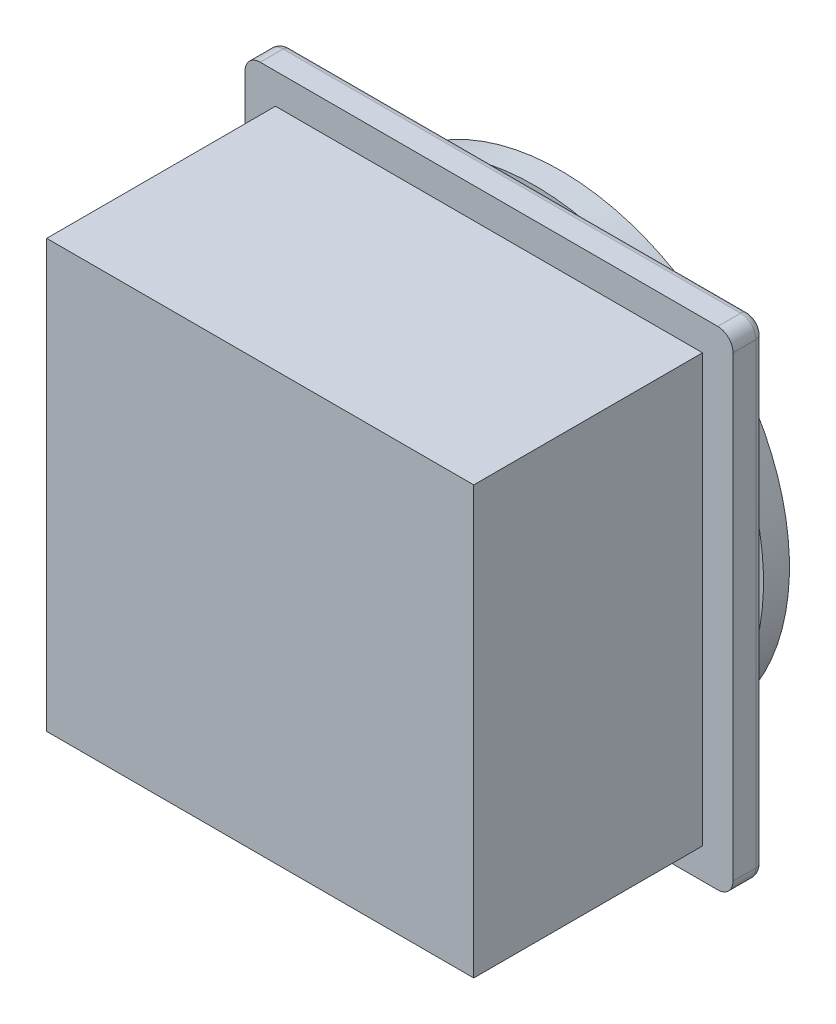
SolidWorks part; units mm, degrees
ref_plane "前视基准面" through (0, 0, 0) normal (0, 0, 1) x (1, 0, 0)
ref_plane "上视基准面" through (0, 0, 0) normal (0, 1, 0) x (1, 0, 0)
ref_plane "右视基准面" through (0, 0, 0) normal (1, 0, 0) x (0, 0, -1)
sketch "草图1" plane through (0, 0, 0) normal (0, 0, 1) x (1, 0, 0)
  line L1 (-140, 140) -> (140, 140)
  line L2 (-140, 140) -> (-140, -140)
  line L3 (-140, -140) -> (140, -140)
  line L4 (140, 140) -> (140, -140)
  line L5 (-140, 140) -> (140, -140) construction
  line L6 (-140, -140) -> (140, 140) construction
  point P0 (0, 0)
  dimension "D1" = 280
  dimension "D2" = 280
extrude "凸台-拉伸1" add sketch "草图1" along normal blind 150
sketch "草图2" plane through (0, -140, 0) normal (0, -1, 0) x (1, 0, 0)
  line L0 (-100.8552, 105.7202) -> (-100.8552, 55.7202)
  line L1 (-95.8552, 55.7202) -> (-95.8552, 105.7202)
  line L4 (-70.8552, 105.7202) -> (-70.8552, 55.7202)
  line L5 (-65.8552, 55.7202) -> (-65.8552, 105.7202)
  line L6 (-40.8552, 105.7202) -> (-40.8552, 55.7202)
  line L7 (-35.8552, 55.7202) -> (-35.8552, 105.7202)
  line L8 (-10.8552, 105.7202) -> (-10.8552, 55.7202)
  line L9 (-5.8552, 55.7202) -> (-5.8552, 105.7202)
  line L10 (19.1448, 105.7202) -> (19.1448, 55.7202)
  line L11 (24.1448, 55.7202) -> (24.1448, 105.7202)
  line L12 (49.1448, 105.7202) -> (49.1448, 55.7202)
  line L13 (54.1448, 55.7202) -> (54.1448, 105.7202)
  line L14 (79.1448, 105.7202) -> (79.1448, 55.7202)
  line L15 (84.1448, 55.7202) -> (84.1448, 105.7202)
  line L16 (109.1448, 105.7202) -> (109.1448, 55.7202)
  line L17 (114.1448, 55.7202) -> (114.1448, 105.7202)
  arc A0 (-100.8552, 55.7202) -> (-95.8552, 55.7202) centre (-98.3552, 55.7202) ccw
  arc A1 (-95.8552, 105.7202) -> (-100.8552, 105.7202) centre (-98.3552, 105.7202) ccw
  arc A2 (-65.8552, 105.7202) -> (-70.8552, 105.7202) centre (-68.3552, 105.7202) ccw
  arc A3 (-70.8552, 55.7202) -> (-65.8552, 55.7202) centre (-68.3552, 55.7202) ccw
  arc A4 (-35.8552, 105.7202) -> (-40.8552, 105.7202) centre (-38.3552, 105.7202) ccw
  arc A5 (-40.8552, 55.7202) -> (-35.8552, 55.7202) centre (-38.3552, 55.7202) ccw
  arc A6 (-5.8552, 105.7202) -> (-10.8552, 105.7202) centre (-8.3552, 105.7202) ccw
  arc A7 (-10.8552, 55.7202) -> (-5.8552, 55.7202) centre (-8.3552, 55.7202) ccw
  arc A8 (24.1448, 105.7202) -> (19.1448, 105.7202) centre (21.6448, 105.7202) ccw
  arc A9 (19.1448, 55.7202) -> (24.1448, 55.7202) centre (21.6448, 55.7202) ccw
  arc A10 (54.1448, 105.7202) -> (49.1448, 105.7202) centre (51.6448, 105.7202) ccw
  arc A11 (49.1448, 55.7202) -> (54.1448, 55.7202) centre (51.6448, 55.7202) ccw
  arc A12 (84.1448, 105.7202) -> (79.1448, 105.7202) centre (81.6448, 105.7202) ccw
  arc A13 (79.1448, 55.7202) -> (84.1448, 55.7202) centre (81.6448, 55.7202) ccw
  arc A14 (114.1448, 105.7202) -> (109.1448, 105.7202) centre (111.6448, 105.7202) ccw
  arc A15 (109.1448, 55.7202) -> (114.1448, 55.7202) centre (111.6448, 55.7202) ccw
  dimension "D1" = 5
  dimension "D3" = 8
  dimension "D2" = 50
shell "抽壳2" thickness 10
extrude "切除-拉伸2" cut sketch "草图2" against normal blind 10
sketch "草图3" plane through (0, 0, 0) normal (0, 0, -1) x (-1, 0, 0)
  line L8 (-160, 160) -> (-160, -160)
  line L9 (-160, -160) -> (160, -160)
  line L10 (160, -160) -> (160, 160)
  line L11 (160, 160) -> (-160, 160)
  line L12 (-160, 160) -> (-160, -160)
  line L13 (-160, -160) -> (160, -160)
  line L14 (160, -160) -> (160, 160)
  line L15 (160, 160) -> (-160, 160)
  dimension "D1" = 20
extrude "凸台-拉伸2" add sketch "草图3" along normal blind 20
fillet "圆角1" radius 10 1 edges at (-160, -160, -10)
fillet "圆角2" radius 10 3 edges at (160, -160, -10) (160, 160, -10) (-160, 160, -10)
fillet "圆角3" radius 5 8 edges at (157.0711, 157.0711, -20) (0, 160, -20) (-157.0711, 157.0711, -20) (-160, 0, -20) (-157.0711, -157.0711, -20) (0, -160, -20) (157.0711, -157.0711, -20) (160, 0, -20)
sketch "草图4" plane through (0, 0, -20) normal (0, 0, -1) x (-1, 0, 0)
  circle A0 centre (0, 0) radius 75
extrude "凸台-拉伸3" add sketch "草图4" along normal blind 10
sketch "草图5" plane through (0, 0, -30) normal (0, 0, -1) x (-1, 0, 0)
  circle A2 centre (0, 0) radius 150
  circle A3 centre (0, 0) radius 150
  dimension "D1" = 75
extrude "凸台-拉伸4" add sketch "草图5" along normal blind 17
sketch "草图6" plane through (0, 0, -20) normal (0, 0, -1) x (-1, 0, 0)
  line L0 (0, 155) -> (0, -165.7949) construction
  line L1 (150, 155) -> (-150, 155) construction
  line L2 (-155, 0) -> (198.8852, 0) construction
  line L3 (-155, 150) -> (-155, -150) construction
  circle A0 centre (-124.6495, 125) radius 5
  circle A1 centre (124.6495, 125) radius 5
  circle A2 centre (124.6495, -125) radius 5
  circle A3 centre (-124.6495, -125) radius 5
extrude "凸台-拉伸5" add sketch "草图6" along normal blind 3
fillet "圆角6" radius 1 1 edges at (129.6495, -125, -23)
fillet "圆角7" radius 1 1 edges at (-129.6495, -125, -23)
fillet "圆角8" radius 1 2 edges at (119.6495, 125, -23) (-119.6495, 125, -23)
ref_plane "基准面4" through (0, 0, 0) normal (0, -1, 0) x (-1, 0, 0)
ref_plane "基准面5" through (0, 0, 0) normal (-1, 0, 0) x (0, 0, 1)
sketch "草图7" plane through (0, 0, -23) normal (0, 0, -1) x (-1, 0, 0)
  line L0 (-124.6495, 125) -> (-124.6495, 130.8243) construction
  line L1 (-124.6495, 125) -> (-118.2393, 125) construction
  line L2 (-125.1495, 127.9121) -> (-124.1495, 127.9121)
  line L3 (-121.4444, 124.5) -> (-121.4444, 125.5)
  line L4 (-121.4444, 125.5) -> (-124.1495, 125.5)
  line L5 (-124.1495, 125.5) -> (-124.1495, 127.9121)
  line L6 (-121.4444, 124.5) -> (-124.1495, 124.5)
  line L7 (-124.1495, 124.5) -> (-124.1495, 122.0879)
  line L8 (-125.1495, 122.0879) -> (-124.1495, 122.0879)
  line L9 (-127.8546, 124.5) -> (-125.1495, 124.5)
  line L10 (-127.8546, 124.5) -> (-127.8546, 125.5)
  line L11 (-127.8546, 125.5) -> (-125.1495, 125.5)
  line L12 (-125.1495, 124.5) -> (-125.1495, 122.0879)
  line L13 (-125.1495, 125.5) -> (-125.1495, 127.9121)
  point P10 (-121.4444, 125)
  point P18 (-124.6495, 122.0879)
  point P19 (-124.6495, 127.9121)
extrude "切除-拉伸3" cut sketch "草图7" against normal blind 1
mirror "镜向1" about plane through (0, 0, 0) normal (0, -1, 0) of "切除-拉伸3"
mirror "镜向2" about plane through (0, 0, 0) normal (-1, 0, 0) of "镜向1", "切除-拉伸3"
